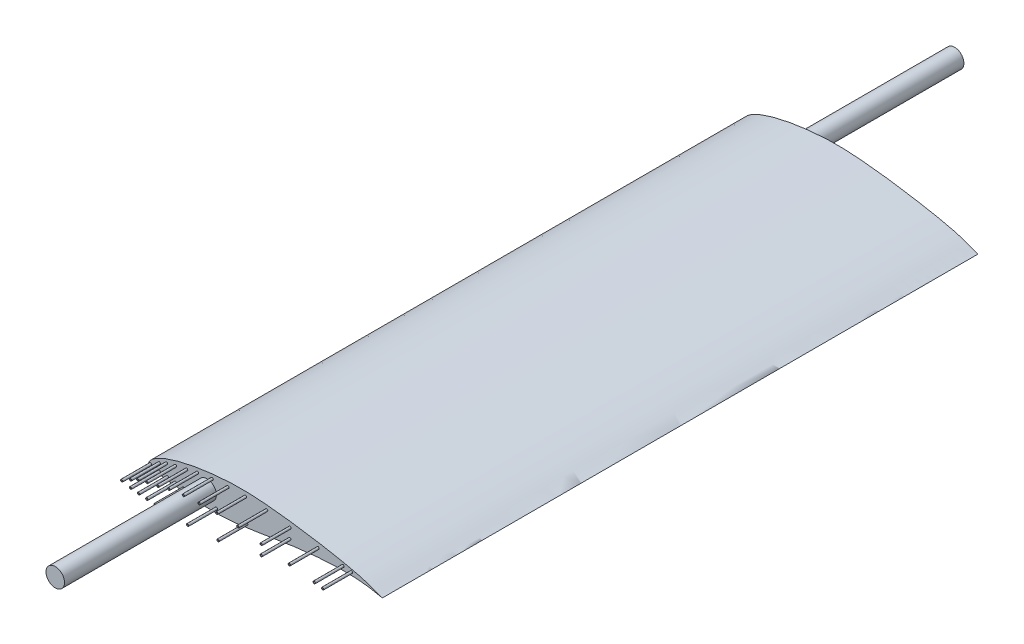
SolidWorks part; units mm, degrees
ref_plane "Front Plane" through (0, 0, 0) normal (0, 0, 1) x (1, 0, 0)
ref_plane "Top Plane" through (0, 0, 0) normal (0, 1, 0) x (1, 0, 0)
ref_plane "Right Plane" through (0, 0, 0) normal (1, 0, 0) x (0, 0, -1)
curve "Curve3"
  spline degree 3 poles (99.2573, 0.1883, 0) (100.1824, -0.0489, 0) (99.2961, 0.1993, 0) (98.6191, 0.462, 0) (97.0519, 1.0473, 0) (95.2309, 1.7549, 0) (92.9378, 2.5568, 0) (90.2536, 3.3336, 0) (87.1477, 4.0816, 0) (83.6535, 4.8449, 0) (79.8051, 5.6126, 0) (75.6551, 6.3782, 0) (71.2568, 7.1284, 0) (66.6666, 7.8484, 0) (61.9423, 8.5212, 0) (57.142, 9.1269, 0) (52.3233, 9.6447, 0) (47.5422, 10.0467, 0) (42.8474, 10.3157, 0) (38.2509, 10.3642, 0) (33.7665, 10.1859, 0) (29.4045, 9.86, 0) (25.2057, 9.3963, 0) (21.2146, 8.8145, 0) (17.4732, 8.1296, 0) (14.0211, 7.3557, 0) (10.8932, 6.51, 0) (8.1211, 5.6039, 0) (5.7296, 4.6586, 0) (3.7392, 3.6865, 0) (2.1629, 2.7162, 0) (1.0057, 1.7671, 0) (0.3099, 0.9241, 0) (0.0336, 0.3269, 0) (0.0006, 0.059, 0) (-0.0005, -0.0441, 0) (0.0087, -0.1472, 0) (0.0976, -0.2807, 0) (0.2176, -0.4056, 0) (0.6069, -0.7185, 0) (1.5156, -1.1239, 0) (3.0705, -1.583, 0) (5.1523, -2.0072, 0) (7.7279, -2.3917, 0) (10.7759, -2.7499, 0) (14.2511, -3.0772, 0) (18.0407, -3.4773, 0) (22.0414, -3.9067, 0) (26.2166, -4.1171, 0) (30.5565, -4.0983, 0) (35.1014, -3.8476, 0) (39.8555, -3.2929, 0) (44.8531, -2.5697, 0) (50.0777, -1.6972, 0) (55.4969, -0.8089, 0) (61.0345, 0.0244, 0) (66.5901, 0.7423, 0) (72.0549, 1.3013, 0) (77.3167, 1.6728, 0) (82.2608, 1.8417, 0) (86.7784, 1.812, 0) (90.7289, 1.5797, 0) (94.0476, 1.182, 0) (96.5243, 0.7715, 0) (98.476, 0.3569, 0) (99.2573, 0.1883, 0) (100.1824, -0.0489, 0) (99.2961, 0.1993, 0) knots -0.015875 -0.006971 -0.001726 0 0.001709 0.006655 0.014348 0.024259 0.036042 0.049641 0.065255 0.082793 0.102031 0.122721 0.144597 0.167375 0.190768 0.214483 0.238233 0.261741 0.284747 0.307088 0.329034 0.350455 0.371139 0.39089 0.409512 0.426831 0.442689 0.45695 0.469523 0.480322 0.48935 0.49658 0.502135 0.505254 0.506016 0.506063 0.506764 0.507486 0.508356 0.509304 0.514776 0.522722 0.53308 0.54584 0.560863 0.578018 0.596961 0.616675 0.636937 0.658148 0.680211 0.703561 0.728221 0.754164 0.781136 0.808649 0.836174 0.86317 0.889092 0.913409 0.935618 0.955187 0.97148 0.984125 0.993029 0.998274 1 1.001709 1.006655 1.014348 periodic
sketch "Sketch4" plane through (0, 0, 0) normal (0, 0, 1) x (1, 0, 0)
  spline S0 degree 3 poles (99.2573, 0.1883) (100.1824, -0.0489) (99.2961, 0.1993) (98.6191, 0.462) (97.0519, 1.0473) (95.2309, 1.7549) (92.9378, 2.5568) (90.2536, 3.3336) (87.1477, 4.0816) (83.6535, 4.8449) (79.8051, 5.6126) (75.6551, 6.3782) (71.2568, 7.1284) (66.6666, 7.8484) (61.9423, 8.5212) (57.142, 9.1269) (52.3233, 9.6447) (47.5422, 10.0467) (42.8474, 10.3157) (38.2509, 10.3642) (33.7665, 10.1859) (29.4045, 9.86) (25.2057, 9.3963) (21.2146, 8.8145) (17.4732, 8.1296) (14.0211, 7.3557) (10.8932, 6.51) (8.1211, 5.6039) (5.7296, 4.6586) (3.7392, 3.6865) (2.1629, 2.7162) (1.0057, 1.7671) (0.3099, 0.9241) (0.0336, 0.3269) (0.0006, 0.059) (-0.0005, -0.0441) (0.0087, -0.1472) (0.0976, -0.2807) (0.2176, -0.4056) (0.6069, -0.7185) (1.5156, -1.1239) (3.0705, -1.583) (5.1523, -2.0072) (7.7279, -2.3917) (10.7759, -2.7499) (14.2511, -3.0772) (18.0407, -3.4773) (22.0414, -3.9067) (26.2166, -4.1171) (30.5565, -4.0983) (35.1014, -3.8476) (39.8555, -3.2929) (44.8531, -2.5697) (50.0777, -1.6972) (55.4969, -0.8089) (61.0345, 0.0244) (66.5901, 0.7423) (72.0549, 1.3013) (77.3167, 1.6728) (82.2608, 1.8417) (86.7784, 1.812) (90.7289, 1.5797) (94.0476, 1.182) (96.5243, 0.7715) (98.476, 0.3569) (99.2573, 0.1883) (100.1824, -0.0489) (99.2961, 0.1993) knots -0.015875 -0.006971 -0.001726 0 0.001709 0.006655 0.014348 0.024259 0.036042 0.049641 0.065255 0.082793 0.102031 0.122721 0.144597 0.167375 0.190768 0.214483 0.238233 0.261741 0.284747 0.307088 0.329034 0.350455 0.371139 0.39089 0.409512 0.426831 0.442689 0.45695 0.469523 0.480322 0.48935 0.49658 0.502135 0.505254 0.506016 0.506063 0.506764 0.507486 0.508356 0.509304 0.514776 0.522722 0.53308 0.54584 0.560863 0.578018 0.596961 0.616675 0.636937 0.658148 0.680211 0.703561 0.728221 0.754164 0.781136 0.808649 0.836174 0.86317 0.889092 0.913409 0.935618 0.955187 0.97148 0.984125 0.993029 0.998274 1 1.001709 1.006655 1.014348 only from (100, 0) to (100, 0) construction
  spline S1 degree 3 poles (99.2573, 0.1883) (100.1824, -0.0489) (99.2961, 0.1993) (98.6191, 0.462) (97.0519, 1.0473) (95.2309, 1.7549) (92.9378, 2.5568) (90.2536, 3.3336) (87.1477, 4.0816) (83.6535, 4.8449) (79.8051, 5.6126) (75.6551, 6.3782) (71.2568, 7.1284) (66.6666, 7.8484) (61.9423, 8.5212) (57.142, 9.1269) (52.3233, 9.6447) (47.5422, 10.0467) (42.8474, 10.3157) (38.2509, 10.3642) (33.7665, 10.1859) (29.4045, 9.86) (25.2057, 9.3963) (21.2146, 8.8145) (17.4732, 8.1296) (14.0211, 7.3557) (10.8932, 6.51) (8.1211, 5.6039) (5.7296, 4.6586) (3.7392, 3.6865) (2.1629, 2.7162) (1.0057, 1.7671) (0.3099, 0.9241) (0.0336, 0.3269) (0.0006, 0.059) (-0.0005, -0.0441) (0.0087, -0.1472) (0.0976, -0.2807) (0.2176, -0.4056) (0.6069, -0.7185) (1.5156, -1.1239) (3.0705, -1.583) (5.1523, -2.0072) (7.7279, -2.3917) (10.7759, -2.7499) (14.2511, -3.0772) (18.0407, -3.4773) (22.0414, -3.9067) (26.2166, -4.1171) (30.5565, -4.0983) (35.1014, -3.8476) (39.8555, -3.2929) (44.8531, -2.5697) (50.0777, -1.6972) (55.4969, -0.8089) (61.0345, 0.0244) (66.5901, 0.7423) (72.0549, 1.3013) (77.3167, 1.6728) (82.2608, 1.8417) (86.7784, 1.812) (90.7289, 1.5797) (94.0476, 1.182) (96.5243, 0.7715) (98.476, 0.3569) (99.2573, 0.1883) (100.1824, -0.0489) (99.2961, 0.1993) knots -0.015875 -0.006971 -0.001726 0 0.001709 0.006655 0.014348 0.024259 0.036042 0.049641 0.065255 0.082793 0.102031 0.122721 0.144597 0.167375 0.190768 0.214483 0.238233 0.261741 0.284747 0.307088 0.329034 0.350455 0.371139 0.39089 0.409512 0.426831 0.442689 0.45695 0.469523 0.480322 0.48935 0.49658 0.502135 0.505254 0.506016 0.506063 0.506764 0.507486 0.508356 0.509304 0.514776 0.522722 0.53308 0.54584 0.560863 0.578018 0.596961 0.616675 0.636937 0.658148 0.680211 0.703561 0.728221 0.754164 0.781136 0.808649 0.836174 0.86317 0.889092 0.913409 0.935618 0.955187 0.97148 0.984125 0.993029 0.998274 1 1.001709 1.006655 1.014348 only from (100, 0) to (100, 0)
extrude "Boss-Extrude12" add sketch "Sketch4" along normal mid plane 255
sketch "Sketch5" plane through (0, 0, 127.5) normal (0, 0, 1) x (1, 0, 0)
  line L0 (100, 0) -> (100, 7.5325) construction
  circle A1 centre (25, 2.7) radius 3.9688
  spline S0 degree 3 poles (99.2573, 0.1883) (100.1824, -0.0489) (99.2961, 0.1993) (98.6191, 0.462) (97.0519, 1.0473) (95.2309, 1.7549) (92.9378, 2.5568) (90.2536, 3.3336) (87.1477, 4.0816) (83.6535, 4.8449) (79.8051, 5.6126) (75.6551, 6.3782) (71.2568, 7.1284) (66.6666, 7.8484) (61.9423, 8.5212) (57.142, 9.1269) (52.3233, 9.6447) (47.5422, 10.0467) (42.8474, 10.3157) (38.2509, 10.3642) (33.7665, 10.1859) (29.4045, 9.86) (25.2057, 9.3963) (21.2146, 8.8145) (17.4732, 8.1296) (14.0211, 7.3557) (10.8932, 6.51) (8.1211, 5.6039) (5.7296, 4.6586) (3.7392, 3.6865) (2.1629, 2.7162) (1.0057, 1.7671) (0.3099, 0.9241) (0.0336, 0.3269) (0.0006, 0.059) (-0.0005, -0.0441) (0.0087, -0.1472) (0.0976, -0.2807) (0.2176, -0.4056) (0.6069, -0.7185) (1.5156, -1.1239) (3.0705, -1.583) (5.1523, -2.0072) (7.7279, -2.3917) (10.7759, -2.7499) (14.2511, -3.0772) (18.0407, -3.4773) (22.0414, -3.9067) (26.2166, -4.1171) (30.5565, -4.0983) (35.1014, -3.8476) (39.8555, -3.2929) (44.8531, -2.5697) (50.0777, -1.6972) (55.4969, -0.8089) (61.0345, 0.0244) (66.5901, 0.7423) (72.0549, 1.3013) (77.3167, 1.6728) (82.2608, 1.8417) (86.7784, 1.812) (90.7289, 1.5797) (94.0476, 1.182) (96.5243, 0.7715) (98.476, 0.3569) (99.2573, 0.1883) (100.1824, -0.0489) (99.2961, 0.1993) knots -0.015875 -0.006971 -0.001726 0 0.001709 0.006655 0.014348 0.024259 0.036042 0.049641 0.065255 0.082793 0.102031 0.122721 0.144597 0.167375 0.190768 0.214483 0.238233 0.261741 0.284747 0.307088 0.329034 0.350455 0.371139 0.39089 0.409512 0.426831 0.442689 0.45695 0.469523 0.480322 0.48935 0.49658 0.502135 0.505254 0.506016 0.506063 0.506764 0.507486 0.508356 0.509304 0.514776 0.522722 0.53308 0.54584 0.560863 0.578018 0.596961 0.616675 0.636937 0.658148 0.680211 0.703561 0.728221 0.754164 0.781136 0.808649 0.836174 0.86317 0.889092 0.913409 0.935618 0.955187 0.97148 0.984125 0.993029 0.998274 1 1.001709 1.006655 1.014348 only from (100, 0) to (100, 0) construction
  dimension "D4" = 7.9375
  dimension "D1" = 100
  dimension "D2" = 25
  dimension "D3" = 2.7
extrude "Boss-Extrude13" add sketch "Sketch5" along normal blind 65
mirror "Mirror1" about plane through (0, 0, 0) normal (0, 0, 1) of "Boss-Extrude13"
sketch "Sketch6" plane through (0, 0, 127.5) normal (0, 0, 1) x (1, 0, 0)
  line L0 (51.5475, 9.6988) -> (56.9104, 9.1388) construction
  line L1 (41.449, 10.3172) -> (44.1311, 10.2279) construction
  circle A0 centre (0.75, 0) radius 0.495
  circle A1 centre (0.75, 0) radius 0.325
  circle A2 centre (86.76, 3) radius 0.495
  circle A3 centre (86.76, 3) radius 0.325
  circle A4 centre (83.16, 3.5) radius 0.495
  circle A5 centre (83.16, 3.5) radius 0.325
  circle A6 centre (72.5, 4.8) radius 0.495
  circle A7 centre (72.5, 4.8) radius 0.325
  circle A8 centre (60.4429, 6.3) radius 0.495
  circle A9 centre (60.4429, 6.3) radius 0.325
  circle A10 centre (60.4429, 2.15) radius 0.495
  circle A11 centre (60.4429, 2.15) radius 0.325
  circle A12 centre (50.4652, 7.8009) radius 0.495
  circle A13 centre (50.4652, 7.8009) radius 0.325
  circle A14 centre (41.4199, 8.317) radius 0.495
  circle A15 centre (41.4199, 8.317) radius 0.325
  circle A16 centre (41.4199, 8.317) radius 0.495
  circle A17 centre (41.4199, 8.317) radius 0.325
  circle A18 centre (33.8799, 8.117) radius 0.495
  circle A19 centre (33.8799, 8.117) radius 0.325
  circle A20 centre (27.1399, 7.767) radius 0.495
  circle A21 centre (27.1399, 7.767) radius 0.325
  circle A22 centre (20.9099, 6.967) radius 0.495
  circle A23 centre (20.9099, 6.967) radius 0.325
  circle A26 centre (16.221, 5.767) radius 0.495
  circle A27 centre (16.221, 5.767) radius 0.325
  circle A28 centre (11.4855, 4.767) radius 0.495
  circle A29 centre (11.4855, 4.767) radius 0.325
  circle A30 centre (7.6125, 3.767) radius 0.495
  circle A31 centre (7.6125, 3.767) radius 0.325
  circle A36 centre (4.5056, 2.267) radius 0.495
  circle A37 centre (4.5056, 2.267) radius 0.325
  circle A38 centre (4.5056, -0.85) radius 0.495
  circle A39 centre (4.5056, -0.85) radius 0.325
  circle A40 centre (7.9928, -1.15) radius 0.495
  circle A41 centre (7.9928, -1.15) radius 0.325
  circle A42 centre (11.4799, -1.45) radius 0.495
  circle A43 centre (11.4799, -1.45) radius 0.325
  circle A44 centre (14.9569, -1.85) radius 0.495
  circle A45 centre (14.9569, -1.85) radius 0.325
  circle A46 centre (28.948, -2.35) radius 0.495
  circle A47 centre (28.948, -2.35) radius 0.325
  circle A48 centre (41.9234, -1.55) radius 0.495
  circle A49 centre (41.9234, -1.55) radius 0.325
  spline S2 degree 3 poles (99.2573, 0.1883) (100.1824, -0.0489) (99.2961, 0.1993) (98.6191, 0.462) (97.0519, 1.0473) (95.2309, 1.7549) (92.9378, 2.5568) (90.2536, 3.3336) (87.1477, 4.0816) (83.6535, 4.8449) (79.8051, 5.6126) (75.6551, 6.3782) (71.2568, 7.1284) (66.6666, 7.8484) (61.9423, 8.5212) (57.142, 9.1269) (52.3233, 9.6447) (47.5422, 10.0467) (42.8474, 10.3157) (38.2509, 10.3642) (33.7665, 10.1859) (29.4045, 9.86) (25.2057, 9.3963) (21.2146, 8.8145) (17.4732, 8.1296) (14.0211, 7.3557) (10.8932, 6.51) (8.1211, 5.6039) (5.7296, 4.6586) (3.7392, 3.6865) (2.1629, 2.7162) (1.0057, 1.7671) (0.3099, 0.9241) (0.0336, 0.3269) (0.0006, 0.059) (-0.0005, -0.0441) (0.0087, -0.1472) (0.0976, -0.2807) (0.2176, -0.4056) (0.6069, -0.7185) (1.5156, -1.1239) (3.0705, -1.583) (5.1523, -2.0072) (7.7279, -2.3917) (10.7759, -2.7499) (14.2511, -3.0772) (18.0407, -3.4773) (22.0414, -3.9067) (26.2166, -4.1171) (30.5565, -4.0983) (35.1014, -3.8476) (39.8555, -3.2929) (44.8531, -2.5697) (50.0777, -1.6972) (55.4969, -0.8089) (61.0345, 0.0244) (66.5901, 0.7423) (72.0549, 1.3013) (77.3167, 1.6728) (82.2608, 1.8417) (86.7784, 1.812) (90.7289, 1.5797) (94.0476, 1.182) (96.5243, 0.7715) (98.476, 0.3569) (99.2573, 0.1883) (100.1824, -0.0489) (99.2961, 0.1993) knots -0.015875 -0.006971 -0.001726 0 0.001709 0.006655 0.014348 0.024259 0.036042 0.049641 0.065255 0.082793 0.102031 0.122721 0.144597 0.167375 0.190768 0.214483 0.238233 0.261741 0.284747 0.307088 0.329034 0.350455 0.371139 0.39089 0.409512 0.426831 0.442689 0.45695 0.469523 0.480322 0.48935 0.49658 0.502135 0.505254 0.506016 0.506063 0.506764 0.507486 0.508356 0.509304 0.514776 0.522722 0.53308 0.54584 0.560863 0.578018 0.596961 0.616675 0.636937 0.658148 0.680211 0.703561 0.728221 0.754164 0.781136 0.808649 0.836174 0.86317 0.889092 0.913409 0.935618 0.955187 0.97148 0.984125 0.993029 0.998274 1 1.001709 1.006655 1.014348 only from (100, 0) to (100, 0) construction
  spline S3 degree 3 poles (99.2573, 0.1883) (100.1824, -0.0489) (99.2961, 0.1993) (98.6191, 0.462) (97.0519, 1.0473) (95.2309, 1.7549) (92.9378, 2.5568) (90.2536, 3.3336) (87.1477, 4.0816) (83.6535, 4.8449) (79.8051, 5.6126) (75.6551, 6.3782) (71.2568, 7.1284) (66.6666, 7.8484) (61.9423, 8.5212) (57.142, 9.1269) (52.3233, 9.6447) (47.5422, 10.0467) (42.8474, 10.3157) (38.2509, 10.3642) (33.7665, 10.1859) (29.4045, 9.86) (25.2057, 9.3963) (21.2146, 8.8145) (17.4732, 8.1296) (14.0211, 7.3557) (10.8932, 6.51) (8.1211, 5.6039) (5.7296, 4.6586) (3.7392, 3.6865) (2.1629, 2.7162) (1.0057, 1.7671) (0.3099, 0.9241) (0.0336, 0.3269) (0.0006, 0.059) (-0.0005, -0.0441) (0.0087, -0.1472) (0.0976, -0.2807) (0.2176, -0.4056) (0.6069, -0.7185) (1.5156, -1.1239) (3.0705, -1.583) (5.1523, -2.0072) (7.7279, -2.3917) (10.7759, -2.7499) (14.2511, -3.0772) (18.0407, -3.4773) (22.0414, -3.9067) (26.2166, -4.1171) (30.5565, -4.0983) (35.1014, -3.8476) (39.8555, -3.2929) (44.8531, -2.5697) (50.0777, -1.6972) (55.4969, -0.8089) (61.0345, 0.0244) (66.5901, 0.7423) (72.0549, 1.3013) (77.3167, 1.6728) (82.2608, 1.8417) (86.7784, 1.812) (90.7289, 1.5797) (94.0476, 1.182) (96.5243, 0.7715) (98.476, 0.3569) (99.2573, 0.1883) (100.1824, -0.0489) (99.2961, 0.1993) knots -0.015875 -0.006971 -0.001726 0 0.001709 0.006655 0.014348 0.024259 0.036042 0.049641 0.065255 0.082793 0.102031 0.122721 0.144597 0.167375 0.190768 0.214483 0.238233 0.261741 0.284747 0.307088 0.329034 0.350455 0.371139 0.39089 0.409512 0.426831 0.442689 0.45695 0.469523 0.480322 0.48935 0.49658 0.502135 0.505254 0.506016 0.506063 0.506764 0.507486 0.508356 0.509304 0.514776 0.522722 0.53308 0.54584 0.560863 0.578018 0.596961 0.616675 0.636937 0.658148 0.680211 0.703561 0.728221 0.754164 0.781136 0.808649 0.836174 0.86317 0.889092 0.913409 0.935618 0.955187 0.97148 0.984125 0.993029 0.998274 1 1.001709 1.006655 1.014348 only from (100, 0) to (100, 0)
  dimension "D1" = 0.99
  dimension "D2" = 0.75
  dimension "D3" = 0.65
  dimension "D4" = 0.99
  dimension "D5" = 0.65
  dimension "D7" = 3
  dimension "D8" = 0.99
  dimension "D11" = 0.65
  dimension "D14" = 0.99
  dimension "D15" = 0.65
  dimension "D16" = 0.99
  dimension "D19" = 0.65
  dimension "D20" = 0.99
  dimension "D21" = 0.65
  dimension "D24" = 0.99
  dimension "D25" = 0.65
  dimension "D28" = 0.99
  dimension "D32" = 0.65
  dimension "D35" = 0.99
  dimension "D36" = 0.65
  dimension "D39" = 0.99
  dimension "D40" = 0.65
  dimension "D42" = 0.99
  dimension "D43" = 0.65
  dimension "D46" = 0.99
  dimension "D47" = 0.65
  dimension "D50" = 0.99
  dimension "D51" = 0.65
  dimension "D54" = 0.99
  dimension "D55" = 0.65
  dimension "D58" = 0.99
  dimension "D59" = 0.65
  dimension "D60" = 0.99
  dimension "D61" = 0.65
  dimension "D62" = 0.99
  dimension "D63" = 0.65
  dimension "D64" = 0.99
  dimension "D65" = 0.65
  dimension "D66" = 0.99
  dimension "D67" = 0.65
  dimension "D68" = 0.65
  dimension "D69" = 0.99
  dimension "D70" = 0.99
  dimension "D71" = 0.65
  dimension "D6" = 13.24
  dimension "D9" = 3.6
  dimension "D10" = 0.5
  dimension "D12" = 10.66
  dimension "D13" = 1.3
  dimension "D17" = 12.15
  dimension "D18" = 1.5
  dimension "D22" = 4.15
  dimension "D23" = 4.84
  dimension "D26" = 10.09
  dimension "D27" = 1.5009
  dimension "D29" = 9.06
  dimension "D30" = 2
  dimension "D31" = 0.5161
  dimension "D33" = 7.54
  dimension "D34" = 0.2
  dimension "D37" = 6.74
  dimension "D38" = 0.35
  dimension "D41" = 6.23
  dimension "D44" = 0.8
  dimension "D45" = 1.2
  dimension "D48" = 4.84
  dimension "D49" = 1
  dimension "D52" = 4
  dimension "D53" = 1
  dimension "D56" = 3.45
  dimension "D57" = 1.5
  dimension "D72" = 0.85
  dimension "D73" = 3.5
  dimension "D74" = 0.3
  dimension "D75" = 3.5
  dimension "D76" = 0.3
  dimension "D77" = 3.5
  dimension "D78" = 0.4
  dimension "D79" = 14
  dimension "D80" = 0.5
  dimension "D81" = 13
  dimension "D82" = 0.8
extrude "Boss-Extrude14" add sketch "Sketch6" along normal blind 12.3 contours A14 A15 | A12 A13 | A8 A9 | A10 A11 | A6 A7 | A4 A5 | A2 A3 | A18 | A20 | A22 | A23 | A21 | A19 | A26 | A28 | A29 | A27 | A31 | A30 | A40 | A41 | A42 | A43 | A44 | A45 | A46 | A47 | A48 | A49 | A0 | A1 | A36 | A37 | A38 | A39
sketch "Sketch7" plane through (0, 0, 0) normal (0, 1, 0) x (1, 0, 0)
  line L0 (100, -127.5) -> (100, 127.5) construction
  line L1 (100, -192.5) -> (0, -192.5)
  line L2 (100, -192.5) -> (100, 192.5)
  line L3 (100, 192.5) -> (0, 192.5)
  line L4 (0, -192.5) -> (0, 192.5)
  line L5 (28.9688, 192.5) -> (21.0312, 192.5) construction
  line L6 (0, -7.9648) -> (0, 7.9648) construction
  line L7 (21.0312, -192.5) -> (28.9688, -192.5) construction
  line L8 (0, 0) -> (100, 0) construction
  line L10 (0, 25) -> (100, 25)
  line L11 (0, 25) -> (0, -25)
  line L12 (0, -25) -> (100, -25)
  line L13 (100, 25) -> (100, -25)
  line L14 (0, 25) -> (100, -25) construction
  line L15 (0, -25) -> (100, 25) construction
  point P15 (50, 0)
  dimension "D1" = 50
extrude "Cut-Extrude1" [suppressed] cut sketch "Sketch7" against normal through all both and the other way through all contours L4 L10 L2 L3 | L12 L4 L1 L2
shell "Shell1" [suppressed] thickness 0.25
sketch "Wing Extended Distance" [suppressed] plane through (0, 0, 0) normal (0, 0, 1) x (1, 0, 0)
  line L0 (100, 0) -> (0, -36.3997)
  line L1 (100, 0) -> (0, -0.0024)
  line L2 (0, -0.0024) -> (11.6985, -32.1415)
  spline S0 degree 3 poles (99.2573, 0.1883) (100.1824, -0.0489) (99.2961, 0.1993) (98.6191, 0.462) (97.0519, 1.0473) (95.2309, 1.7549) (92.9378, 2.5568) (90.2536, 3.3336) (87.1477, 4.0816) (83.6535, 4.8449) (79.8051, 5.6126) (75.6551, 6.3782) (71.2568, 7.1284) (66.6666, 7.8484) (61.9423, 8.5212) (57.142, 9.1269) (52.3233, 9.6447) (47.5422, 10.0467) (42.8474, 10.3157) (38.2509, 10.3642) (33.7665, 10.1859) (29.4045, 9.86) (25.2057, 9.3963) (21.2146, 8.8145) (17.4732, 8.1296) (14.0211, 7.3557) (10.8932, 6.51) (8.1211, 5.6039) (5.7296, 4.6586) (3.7392, 3.6865) (2.1629, 2.7162) (1.0057, 1.7671) (0.3099, 0.9241) (0.0336, 0.3269) (0.0006, 0.059) (-0.0005, -0.0441) (0.0087, -0.1472) (0.0976, -0.2807) (0.2176, -0.4056) (0.6069, -0.7185) (1.5156, -1.1239) (3.0705, -1.583) (5.1523, -2.0072) (7.7279, -2.3917) (10.7759, -2.7499) (14.2511, -3.0772) (18.0407, -3.4773) (22.0414, -3.9067) (26.2166, -4.1171) (30.5565, -4.0983) (35.1014, -3.8476) (39.8555, -3.2929) (44.8531, -2.5697) (50.0777, -1.6972) (55.4969, -0.8089) (61.0345, 0.0244) (66.5901, 0.7423) (72.0549, 1.3013) (77.3167, 1.6728) (82.2608, 1.8417) (86.7784, 1.812) (90.7289, 1.5797) (94.0476, 1.182) (96.5243, 0.7715) (98.476, 0.3569) (99.2573, 0.1883) (100.1824, -0.0489) (99.2961, 0.1993) knots -0.015875 -0.006971 -0.001726 0 0.001709 0.006655 0.014348 0.024259 0.036042 0.049641 0.065255 0.082793 0.102031 0.122721 0.144597 0.167375 0.190768 0.214483 0.238233 0.261741 0.284747 0.307088 0.329034 0.350455 0.371139 0.39089 0.409512 0.426831 0.442689 0.45695 0.469523 0.480322 0.48935 0.49658 0.502135 0.505254 0.506016 0.506063 0.506764 0.507486 0.508356 0.509304 0.514776 0.522722 0.53308 0.54584 0.560863 0.578018 0.596961 0.616675 0.636937 0.658148 0.680211 0.703561 0.728221 0.754164 0.781136 0.808649 0.836174 0.86317 0.889092 0.913409 0.935618 0.955187 0.97148 0.984125 0.993029 0.998274 1 1.001709 1.006655 1.014348 only from (100, 0) to (100, 0) construction
  dimension "D1" = 20
  dimension "D2" = 34.202
sketch "Sketch8" plane through (0, 0, 192.5) normal (0, 0, 1) x (1, 0, 0)
  line L0 (25, 5.5665) -> (25, 2.7) construction
  line L1 (25, 2.7) -> (22.9381, 2.7) construction
  circle A1 centre (25, 2.7) radius 3.9688
  circle A2 centre (25, 2.7) radius 3.9688
  dimension "D1" = 0
